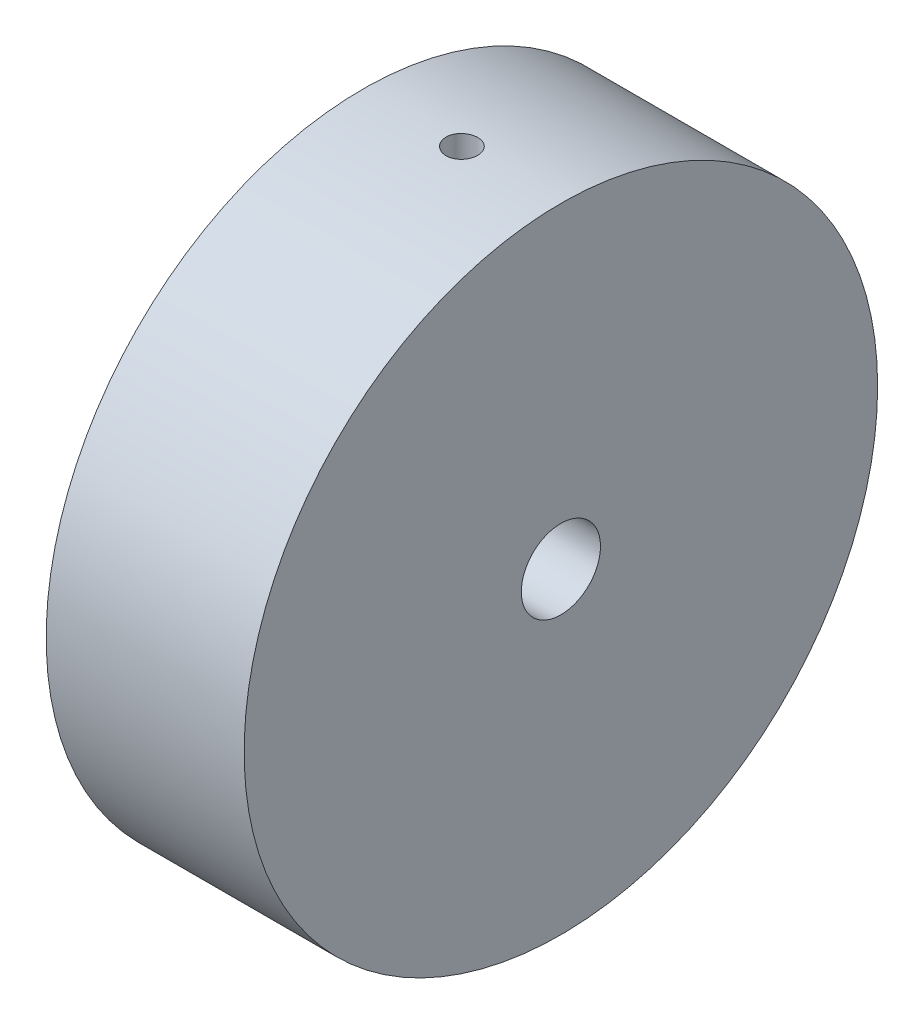
SolidWorks part; units mm, degrees
material "3.1645 (EN AW-2007)"
ref_plane "Plano frontal" through (0, 0, 0) normal (0, 0, 1) x (1, 0, 0)
ref_plane "Plano superior" through (0, 0, 0) normal (0, 1, 0) x (1, 0, 0)
ref_plane "Plano direito" through (0, 0, 0) normal (1, 0, 0) x (0, 0, -1)
sketch "Esboço3" plane through (0, 0, 0) normal (0, 0, 1) x (1, 0, 0)
  line L0 (0, 0) -> (-50.7324, 0) construction
  line L1 (0, 16) -> (0, 2)
  line L2 (-2, 10) -> (-2, 5)
  line L3 (-10, 5) -> (-10, 0)
  line L4 (-2, 5) -> (-10, 5)
  line L5 (-10, 0) -> (-8, 0)
  line L6 (-8, 2) -> (0, 2)
  line L7 (-2, 10) -> (-10, 10)
  line L8 (-10, 10) -> (-10, 16)
  line L9 (-10, 16) -> (0, 16)
  line L10 (-8, 0) -> (-8, 2)
  dimension "D1" = 2
  dimension "D2" = 16
  dimension "D3" = 6
  dimension "D4" = 10
  dimension "D5" = 5
  dimension "D6" = 2
  dimension "D7" = 10
  dimension "D8" = 2
revolve "Revolução1" add sketch "Esboço3" angle 360 about L0
ref_plane "Plano1" through (0, 5, 0) normal (0, 1, 0) x (1, 0, 0)
sketch "Esboço6" plane through (0, 5, 0) normal (0, 1, 0) x (1, 0, 0)
  line L0 (-10, 16) -> (-10, -16) construction
  circle A0 centre (-5, 0) radius 0.8
  dimension "D1" = 1.6
  dimension "D2" = 5
extrude "Corte-extrusão1" cut sketch "Esboço6" against normal mid plane 70
equation "\"D4@Esboço3\"=\"D7@Esboço3\""
